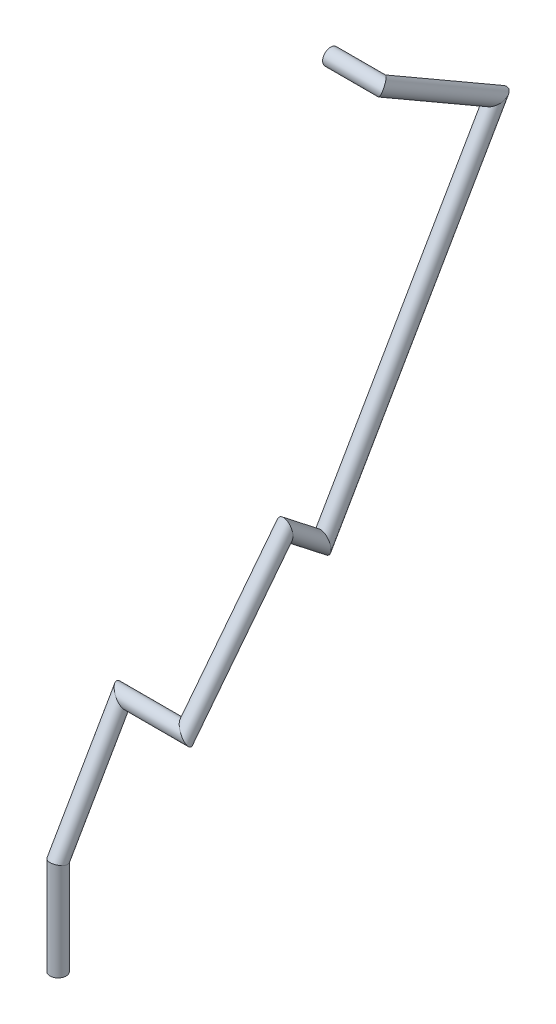
SolidWorks part; units mm, degrees
ref_plane "Front Plane" through (0, 0, 0) normal (0, 0, 1) x (1, 0, 0)
ref_plane "Top Plane" through (0, 0, 0) normal (0, 1, 0) x (1, 0, 0)
ref_plane "Right Plane" through (0, 0, 0) normal (1, 0, 0) x (0, 0, -1)
sketch3d "3DSketch1"
  line L0 (0, 0, 0) -> (0, 30, 0)
  line L1 (0, 30, 0) -> (0, 64.641, -20)
  line L2 (0, 64.641, -20) -> (20, 64.641, -20)
  line L3 (0, 64.641, -20) -> (0, 128.8153, -70.1385) construction
  line L4 (20, 64.641, -20) -> (20, 104.0416, -50.7831)
  line L5 (20, 104.0416, -50.7831) -> (20, 94.8066, -62.6032)
  line L6 (20, 94.8066, -62.6032) -> (20, 188.3374, -116.6032)
  line L7 (20, 104.0416, -50.7831) -> (53.8812, 104.0416, -50.7831) construction
  line L8 (20, 188.3374, -116.6032) -> (20, 208.8374, -81.0962)
  line L9 (20, 208.8374, -81.0962) -> (3.9785, 208.8374, -81.0962)
  dimension "D1" = 30
  dimension "D2" = 150
  dimension "D3" = 40
  dimension "D4" = 20
  dimension "D5" = 172
  dimension "D6" = 50
  dimension "D7" = 15
  dimension "D8" = 108
  dimension "D9" = 41
  dimension "D10" = 90
  dimension "D11" = 90
sweep "Sweep1" add path "3DSketch1" circular profile diameter 5 parameters "D3"=5
